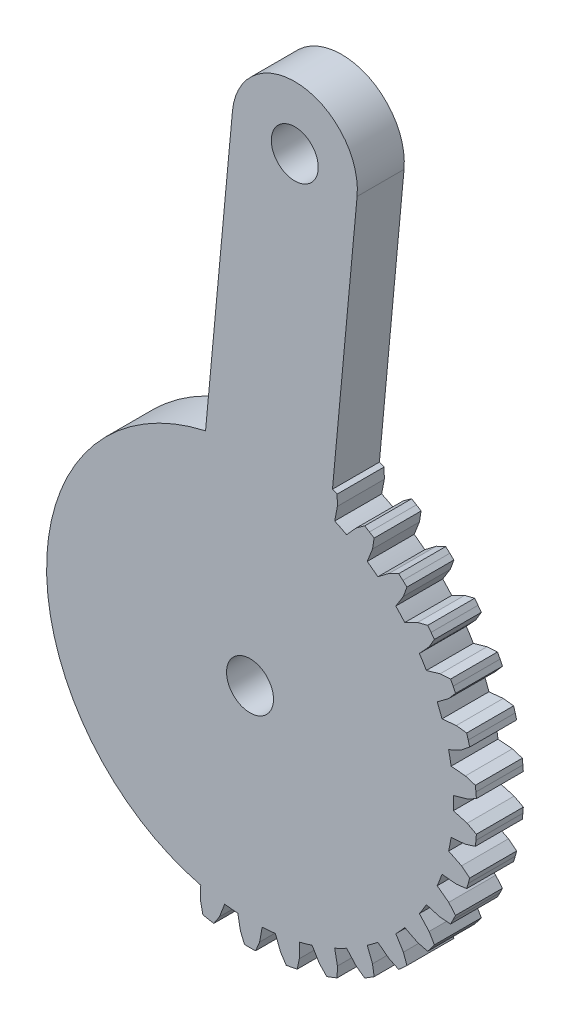
SolidWorks part; units mm, degrees
material "Chrome Stainless Steel"
ref_plane "Front Plane" through (0, 0, 0) normal (0, 0, 1) x (1, 0, 0)
ref_plane "Top Plane" through (0, 0, 0) normal (0, 1, 0) x (1, 0, 0)
ref_plane "Right Plane" through (0, 0, 0) normal (1, 0, 0) x (0, 0, -1)
sketch "Sketch1" plane through (0, 0, 0) normal (0, 0, 1) x (1, 0, 0)
  line L0 (0, 13) -> (0, 14.5) construction
  line L1 (-0.7768, 12.9768) -> (-0.6124, 13.879)
  line L2 (-0.6124, 13.879) -> (-0.3549, 14.4957)
  line L3 (-0.3549, 14.4957) -> (0, 14.5)
  line L4 (0.3549, 14.4957) -> (0, 14.5)
  line L5 (0.7768, 12.9768) -> (0.6124, 13.879)
  line L6 (0.6124, 13.879) -> (0.3549, 14.4957)
  line L7 (1.9483, 13.7552) -> (2.3147, 14.3141)
  line L8 (1.6209, 12.8986) -> (1.9483, 13.7552)
  line L9 (3.1522, 13.5302) -> (3.0124, 14.1836)
  line L10 (3.148, 12.6131) -> (3.1522, 13.5302)
  line L11 (3.0124, 14.1836) -> (2.6644, 14.2531)
  line L12 (2.3147, 14.3141) -> (2.6644, 14.2531)
  line L13 (4.4426, 13.163) -> (4.9055, 13.645)
  line L14 (3.9634, 12.3811) -> (4.4426, 13.163)
  line L15 (5.5847, 12.7206) -> (5.5674, 13.3886)
  line L16 (5.4121, 11.8199) -> (5.5847, 12.7206)
  line L17 (5.5674, 13.3886) -> (5.238, 13.5208)
  line L18 (4.9055, 13.645) -> (5.238, 13.5208)
  line L19 (6.7857, 12.1225) -> (7.3292, 12.5113)
  line L20 (6.1709, 11.442) -> (6.7857, 12.1225)
  line L21 (7.827, 11.4778) -> (7.9327, 12.1376)
  line L22 (7.4918, 10.6241) -> (7.827, 11.4778)
  line L23 (7.9327, 12.1376) -> (7.6333, 12.3281)
  line L24 (7.3292, 12.5113) -> (7.6333, 12.3281)
  line L25 (8.8977, 10.6693) -> (9.5034, 10.9515)
  line L26 (8.1683, 10.1133) -> (8.8977, 10.6693)
  line L27 (9.8028, 9.8441) -> (10.0279, 10.4733)
  line L28 (9.3165, 9.0666) -> (9.8028, 9.8441)
  line L29 (10.0279, 10.4733) -> (9.7686, 10.7156)
  line L30 (9.5034, 10.9515) -> (9.7686, 10.7156)
  line L31 (10.7066, 8.8526) -> (11.3539, 9.0188)
  line L32 (9.8876, 8.4402) -> (10.7066, 8.8526)
  line L33 (11.4447, 7.8753) -> (11.7817, 8.4524)
  line L34 (10.8238, 7.2004) -> (11.4447, 7.8753)
  line L35 (11.7817, 8.4524) -> (11.5712, 8.7382)
  line L36 (11.3539, 9.0188) -> (11.5712, 8.7382)
  line L37 (12.151, 6.7346) -> (12.8178, 6.779)
  line L38 (11.2701, 6.4796) -> (12.151, 6.7346)
  line L39 (12.6969, 5.6382) -> (13.1342, 6.1436)
  line L40 (11.9626, 5.0889) -> (12.6969, 5.6382)
  line L41 (13.1342, 6.1436) -> (12.9799, 6.4632)
  line L42 (12.8178, 6.779) -> (12.9799, 6.4632)
  line L43 (13.1816, 4.3872) -> (13.8452, 4.3083)
  line L44 (12.2688, 4.2984) -> (13.1816, 4.3872)
  line L45 (13.5168, 3.2092) -> (14.0394, 3.6256)
  line L46 (12.694, 2.8041) -> (13.5168, 3.2092)
  line L47 (14.0394, 3.6256) -> (13.9465, 3.9681)
  line L48 (13.8452, 4.3083) -> (13.9465, 3.9681)
  line L49 (13.7633, 1.8904) -> (14.4011, 1.6909)
  line L50 (12.8497, 1.9708) -> (13.7633, 1.8904)
  line L51 (13.8763, 0.6708) -> (14.4666, 0.9841)
  line L52 (12.9931, 0.4239) -> (13.8763, 0.6708)
  line L53 (14.4666, 0.9841) -> (14.4381, 1.3379)
  line L54 (14.4011, 1.6909) -> (14.4381, 1.3379)
  line L55 (13.8763, -0.6708) -> (14.4666, -0.9841)
  line L56 (12.9931, -0.4239) -> (13.8763, -0.6708)
  line L57 (13.7633, -1.8904) -> (14.4011, -1.6909)
  line L58 (12.8497, -1.9708) -> (13.7633, -1.8904)
  line L59 (14.4011, -1.6909) -> (14.4381, -1.3379)
  line L60 (14.4666, -0.9841) -> (14.4381, -1.3379)
  line L61 (13.5168, -3.2092) -> (14.0394, -3.6256)
  line L62 (12.694, -2.8041) -> (13.5168, -3.2092)
  line L63 (13.1816, -4.3872) -> (13.8452, -4.3083)
  line L64 (12.2688, -4.2984) -> (13.1816, -4.3872)
  line L65 (13.8452, -4.3083) -> (13.9465, -3.9681)
  line L66 (14.0394, -3.6256) -> (13.9465, -3.9681)
  line L67 (12.6969, -5.6382) -> (13.1342, -6.1436)
  line L68 (11.9626, -5.0889) -> (12.6969, -5.6382)
  line L69 (12.151, -6.7346) -> (12.8178, -6.779)
  line L70 (11.2701, -6.4796) -> (12.151, -6.7346)
  line L71 (12.8178, -6.779) -> (12.9799, -6.4632)
  line L72 (13.1342, -6.1436) -> (12.9799, -6.4632)
  line L73 (11.4447, -7.8753) -> (11.7817, -8.4524)
  line L74 (10.8238, -7.2004) -> (11.4447, -7.8753)
  line L75 (10.7066, -8.8526) -> (11.3539, -9.0188)
  line L76 (9.8876, -8.4402) -> (10.7066, -8.8526)
  line L77 (11.3539, -9.0188) -> (11.5712, -8.7382)
  line L78 (11.7817, -8.4524) -> (11.5712, -8.7382)
  line L79 (9.8028, -9.8441) -> (10.0279, -10.4733)
  line L80 (9.3165, -9.0666) -> (9.8028, -9.8441)
  line L81 (8.8977, -10.6693) -> (9.5034, -10.9515)
  line L82 (8.1683, -10.1133) -> (8.8977, -10.6693)
  line L83 (9.5034, -10.9515) -> (9.7686, -10.7156)
  line L84 (10.0279, -10.4733) -> (9.7686, -10.7156)
  line L85 (7.827, -11.4778) -> (7.9327, -12.1376)
  line L86 (7.4918, -10.6241) -> (7.827, -11.4778)
  line L87 (6.7857, -12.1225) -> (7.3292, -12.5113)
  line L88 (6.1709, -11.442) -> (6.7857, -12.1225)
  line L89 (7.3292, -12.5113) -> (7.6333, -12.3281)
  line L90 (7.9327, -12.1376) -> (7.6333, -12.3281)
  line L91 (5.5847, -12.7206) -> (5.5674, -13.3886)
  line L92 (5.4121, -11.8199) -> (5.5847, -12.7206)
  line L93 (4.4426, -13.163) -> (4.9055, -13.645)
  line L94 (3.9634, -12.3811) -> (4.4426, -13.163)
  line L95 (4.9055, -13.645) -> (5.238, -13.5208)
  line L96 (5.5674, -13.3886) -> (5.238, -13.5208)
  line L97 (3.1522, -13.5302) -> (3.0124, -14.1836)
  line L98 (3.148, -12.6131) -> (3.1522, -13.5302)
  line L99 (1.9483, -13.7552) -> (2.3147, -14.3141)
  line L100 (1.6209, -12.8986) -> (1.9483, -13.7552)
  line L101 (2.3147, -14.3141) -> (2.6644, -14.2531)
  line L102 (3.0124, -14.1836) -> (2.6644, -14.2531)
  line L103 (0.6124, -13.879) -> (0.3549, -14.4957)
  line L104 (0.7768, -12.9768) -> (0.6124, -13.879)
  line L105 (-0.6124, -13.879) -> (-0.3549, -14.4957)
  line L106 (-0.7768, -12.9768) -> (-0.6124, -13.879)
  line L107 (-0.3549, -14.4957) -> (0, -14.5)
  line L108 (0.3549, -14.4957) -> (0, -14.5)
  line L109 (-1.9483, -13.7552) -> (-2.3147, -14.3141)
  line L110 (-1.6209, -12.8986) -> (-1.9483, -13.7552)
  line L111 (-3.1522, -13.5302) -> (-3.0124, -14.1836)
  line L112 (-3.148, -12.6131) -> (-3.1522, -13.5302)
  line L113 (-3.0124, -14.1836) -> (-2.6644, -14.2531)
  line L114 (-2.3147, -14.3141) -> (-2.6644, -14.2531)
  line L115 (-4.4426, -13.163) -> (-4.9055, -13.645)
  line L116 (-3.9634, -12.3811) -> (-4.4426, -13.163)
  line L117 (-5.5847, -12.7206) -> (-5.5674, -13.3886)
  line L118 (-5.4121, -11.8199) -> (-5.5847, -12.7206)
  line L119 (-5.5674, -13.3886) -> (-5.238, -13.5208)
  line L120 (-4.9055, -13.645) -> (-5.238, -13.5208)
  line L121 (-6.7857, -12.1225) -> (-7.3292, -12.5113)
  line L122 (-6.1709, -11.442) -> (-6.7857, -12.1225)
  line L123 (-7.827, -11.4778) -> (-7.9327, -12.1376)
  line L124 (-7.4918, -10.6241) -> (-7.827, -11.4778)
  line L125 (-7.9327, -12.1376) -> (-7.6333, -12.3281)
  line L126 (-7.3292, -12.5113) -> (-7.6333, -12.3281)
  line L127 (-8.8977, -10.6693) -> (-9.5034, -10.9515)
  line L128 (-8.1683, -10.1133) -> (-8.8977, -10.6693)
  line L129 (-9.8028, -9.8441) -> (-10.0279, -10.4733)
  line L130 (-9.3165, -9.0666) -> (-9.8028, -9.8441)
  line L131 (-10.0279, -10.4733) -> (-9.7686, -10.7156)
  line L132 (-9.5034, -10.9515) -> (-9.7686, -10.7156)
  line L133 (-10.7066, -8.8526) -> (-11.3539, -9.0188)
  line L134 (-9.8876, -8.4402) -> (-10.7066, -8.8526)
  line L135 (-11.4447, -7.8753) -> (-11.7817, -8.4524)
  line L136 (-10.8238, -7.2004) -> (-11.4447, -7.8753)
  line L137 (-11.7817, -8.4524) -> (-11.5712, -8.7382)
  line L138 (-11.3539, -9.0188) -> (-11.5712, -8.7382)
  line L139 (-12.151, -6.7346) -> (-12.8178, -6.779)
  line L140 (-11.2701, -6.4796) -> (-12.151, -6.7346)
  line L141 (-12.6969, -5.6382) -> (-13.1342, -6.1436)
  line L142 (-11.9626, -5.0889) -> (-12.6969, -5.6382)
  line L143 (-13.1342, -6.1436) -> (-12.9799, -6.4632)
  line L144 (-12.8178, -6.779) -> (-12.9799, -6.4632)
  line L145 (-13.1816, -4.3872) -> (-13.8452, -4.3083)
  line L146 (-12.2688, -4.2984) -> (-13.1816, -4.3872)
  line L147 (-13.5168, -3.2092) -> (-14.0394, -3.6256)
  line L148 (-12.694, -2.8041) -> (-13.5168, -3.2092)
  line L149 (-14.0394, -3.6256) -> (-13.9465, -3.9681)
  line L150 (-13.8452, -4.3083) -> (-13.9465, -3.9681)
  line L151 (-13.7633, -1.8904) -> (-14.4011, -1.6909)
  line L152 (-12.8497, -1.9708) -> (-13.7633, -1.8904)
  line L153 (-13.8763, -0.6708) -> (-14.4666, -0.9841)
  line L154 (-12.9931, -0.4239) -> (-13.8763, -0.6708)
  line L155 (-14.4666, -0.9841) -> (-14.4381, -1.3379)
  line L156 (-14.4011, -1.6909) -> (-14.4381, -1.3379)
  line L157 (-13.8763, 0.6708) -> (-14.4666, 0.9841)
  line L158 (-12.9931, 0.4239) -> (-13.8763, 0.6708)
  line L159 (-13.7633, 1.8904) -> (-14.4011, 1.6909)
  line L160 (-12.8497, 1.9708) -> (-13.7633, 1.8904)
  line L161 (-14.4011, 1.6909) -> (-14.4381, 1.3379)
  line L162 (-14.4666, 0.9841) -> (-14.4381, 1.3379)
  line L163 (-13.5168, 3.2092) -> (-14.0394, 3.6256)
  line L164 (-12.694, 2.8041) -> (-13.5168, 3.2092)
  line L165 (-13.1816, 4.3872) -> (-13.8452, 4.3083)
  line L166 (-12.2688, 4.2984) -> (-13.1816, 4.3872)
  line L167 (-13.8452, 4.3083) -> (-13.9465, 3.9681)
  line L168 (-14.0394, 3.6256) -> (-13.9465, 3.9681)
  line L169 (-12.6969, 5.6382) -> (-13.1342, 6.1436)
  line L170 (-11.9626, 5.0889) -> (-12.6969, 5.6382)
  line L171 (-12.151, 6.7346) -> (-12.8178, 6.779)
  line L172 (-11.2701, 6.4796) -> (-12.151, 6.7346)
  line L173 (-12.8178, 6.779) -> (-12.9799, 6.4632)
  line L174 (-13.1342, 6.1436) -> (-12.9799, 6.4632)
  line L175 (-11.4447, 7.8753) -> (-11.7817, 8.4524)
  line L176 (-10.8238, 7.2004) -> (-11.4447, 7.8753)
  line L177 (-10.7066, 8.8526) -> (-11.3539, 9.0188)
  line L178 (-9.8876, 8.4402) -> (-10.7066, 8.8526)
  line L179 (-11.3539, 9.0188) -> (-11.5712, 8.7382)
  line L180 (-11.7817, 8.4524) -> (-11.5712, 8.7382)
  line L181 (-9.8028, 9.8441) -> (-10.0279, 10.4733)
  line L182 (-9.3165, 9.0666) -> (-9.8028, 9.8441)
  line L183 (-8.8977, 10.6693) -> (-9.5034, 10.9515)
  line L184 (-8.1683, 10.1133) -> (-8.8977, 10.6693)
  line L185 (-9.5034, 10.9515) -> (-9.7686, 10.7156)
  line L186 (-10.0279, 10.4733) -> (-9.7686, 10.7156)
  line L187 (-7.827, 11.4778) -> (-7.9327, 12.1376)
  line L188 (-7.4918, 10.6241) -> (-7.827, 11.4778)
  line L189 (-6.7857, 12.1225) -> (-7.3292, 12.5113)
  line L190 (-6.1709, 11.442) -> (-6.7857, 12.1225)
  line L191 (-7.3292, 12.5113) -> (-7.6333, 12.3281)
  line L192 (-7.9327, 12.1376) -> (-7.6333, 12.3281)
  line L193 (-5.5847, 12.7206) -> (-5.5674, 13.3886)
  line L194 (-5.4121, 11.8199) -> (-5.5847, 12.7206)
  line L195 (-4.4426, 13.163) -> (-4.9055, 13.645)
  line L196 (-3.9634, 12.3811) -> (-4.4426, 13.163)
  line L197 (-4.9055, 13.645) -> (-5.238, 13.5208)
  line L198 (-5.5674, 13.3886) -> (-5.238, 13.5208)
  line L199 (-3.1522, 13.5302) -> (-3.0124, 14.1836)
  line L200 (-3.148, 12.6131) -> (-3.1522, 13.5302)
  line L201 (-1.9483, 13.7552) -> (-2.3147, 14.3141)
  line L202 (-1.6209, 12.8986) -> (-1.9483, 13.7552)
  line L203 (-2.3147, 14.3141) -> (-2.6644, 14.2531)
  line L204 (-3.0124, 14.1836) -> (-2.6644, 14.2531)
  circle A0 centre (0, 0) radius 13
  circle A1 centre (0, 0) radius 14.5
  point P12 (0, 0)
  point P13 (0, 0)
  point P246 (0, 0)
  dimension "D1" = 29
  dimension "D2" = 26
  dimension "D3" = 0.3549
  dimension "D4" = 0.6682
  dimension "D5" = 0.9171
  dimension "D7" = 1.3359
  dimension "D8" = 0.8441
  dimension "D9" = 2.6758
  dimension "D6" = 34
extrude "Boss-Extrude1" add sketch "Sketch1" along normal blind 3
sketch "Sketch2" plane through (0, 0, 3) normal (0, 0, 1) x (1, 0, 0)
  circle A0 centre (0, 0) radius 1.5
  dimension "D1" = 3
extrude "Cut-Extrude1" cut sketch "Sketch2" against normal blind 7
sketch "Sketch4" plane through (0, 0, 3) normal (0, 0, 1) x (1, 0, 0)
  line L0 (0, 0) -> (2.8603, 30.8678) construction
  line L1 (-3.9829, 0.3691) -> (-1.1226, 31.2368)
  line L2 (3.9829, -0.3691) -> (6.8433, 30.4987)
  line L3 (0, 0) -> (14.4381, -1.3379) construction
  line L117 (0.3549, 14.4957) -> (0, 14.5)
  line L118 (0, 14.5) -> (-0.3549, 14.4957)
  line L119 (-0.3549, 14.4957) -> (-0.6124, 13.879)
  line L120 (-0.6124, 13.879) -> (-0.7768, 12.9768)
  line L121 (-3.148, -12.6131) -> (-3.1522, -13.5302)
  line L122 (-3.1522, -13.5302) -> (-3.0124, -14.1836)
  line L123 (-3.0124, -14.1836) -> (-2.6644, -14.2531)
  line L124 (-2.6644, -14.2531) -> (-2.3147, -14.3141)
  line L125 (-2.3147, -14.3141) -> (-1.9483, -13.7552)
  line L126 (-1.9483, -13.7552) -> (-1.6209, -12.8986)
  line L127 (-0.7768, -12.9768) -> (-0.6124, -13.879)
  line L128 (-0.6124, -13.879) -> (-0.3549, -14.4957)
  line L129 (-0.3549, -14.4957) -> (0, -14.5)
  line L130 (0, -14.5) -> (0.3549, -14.4957)
  line L131 (0.3549, -14.4957) -> (0.6124, -13.879)
  line L132 (0.6124, -13.879) -> (0.7768, -12.9768)
  line L133 (1.6209, -12.8986) -> (1.9483, -13.7552)
  line L134 (1.9483, -13.7552) -> (2.3147, -14.3141)
  line L135 (2.3147, -14.3141) -> (2.6644, -14.2531)
  line L136 (2.6644, -14.2531) -> (3.0124, -14.1836)
  line L137 (3.0124, -14.1836) -> (3.1522, -13.5302)
  line L138 (3.1522, -13.5302) -> (3.148, -12.6131)
  line L139 (3.9634, -12.3811) -> (4.4426, -13.163)
  line L140 (4.4426, -13.163) -> (4.9055, -13.645)
  line L141 (4.9055, -13.645) -> (5.238, -13.5208)
  line L142 (5.238, -13.5208) -> (5.5674, -13.3886)
  line L143 (5.5674, -13.3886) -> (5.5847, -12.7206)
  line L144 (5.5847, -12.7206) -> (5.4121, -11.8199)
  line L145 (6.1709, -11.442) -> (6.7857, -12.1225)
  line L146 (6.7857, -12.1225) -> (7.3292, -12.5113)
  line L147 (7.3292, -12.5113) -> (7.6333, -12.3281)
  line L148 (7.6333, -12.3281) -> (7.9327, -12.1376)
  line L149 (7.9327, -12.1376) -> (7.827, -11.4778)
  line L150 (7.827, -11.4778) -> (7.4918, -10.6241)
  line L151 (8.1683, -10.1133) -> (8.8977, -10.6693)
  line L152 (8.8977, -10.6693) -> (9.5034, -10.9515)
  line L153 (9.5034, -10.9515) -> (9.7686, -10.7156)
  line L154 (9.7686, -10.7156) -> (10.0279, -10.4733)
  line L155 (10.0279, -10.4733) -> (9.8028, -9.8441)
  line L156 (9.8028, -9.8441) -> (9.3165, -9.0666)
  line L157 (9.8876, -8.4402) -> (10.7066, -8.8526)
  line L158 (10.7066, -8.8526) -> (11.3539, -9.0188)
  line L159 (11.3539, -9.0188) -> (11.5712, -8.7382)
  line L160 (11.5712, -8.7382) -> (11.7817, -8.4524)
  line L161 (11.7817, -8.4524) -> (11.4447, -7.8753)
  line L162 (11.4447, -7.8753) -> (10.8238, -7.2004)
  line L163 (11.2701, -6.4796) -> (12.151, -6.7346)
  line L164 (12.151, -6.7346) -> (12.8178, -6.779)
  line L165 (12.8178, -6.779) -> (12.9799, -6.4632)
  line L166 (12.9799, -6.4632) -> (13.1342, -6.1436)
  line L167 (13.1342, -6.1436) -> (12.6969, -5.6382)
  line L168 (12.6969, -5.6382) -> (11.9626, -5.0889)
  line L169 (12.2688, -4.2984) -> (13.1816, -4.3872)
  line L170 (13.1816, -4.3872) -> (13.8452, -4.3083)
  line L171 (13.8452, -4.3083) -> (13.9465, -3.9681)
  line L172 (13.9465, -3.9681) -> (14.0394, -3.6256)
  line L173 (14.0394, -3.6256) -> (13.5168, -3.2092)
  line L174 (13.5168, -3.2092) -> (12.694, -2.8041)
  line L175 (12.8497, -1.9708) -> (13.7633, -1.8904)
  line L176 (13.7633, -1.8904) -> (14.4011, -1.6909)
  line L177 (14.4011, -1.6909) -> (14.4381, -1.3379)
  line L178 (14.4381, -1.3379) -> (14.4666, -0.9841)
  line L179 (14.4666, -0.9841) -> (13.8763, -0.6708)
  line L180 (13.8763, -0.6708) -> (12.9931, -0.4239)
  line L181 (12.9931, 0.4239) -> (13.8763, 0.6708)
  line L182 (13.8763, 0.6708) -> (14.4666, 0.9841)
  line L183 (14.4666, 0.9841) -> (14.4381, 1.3379)
  line L184 (14.4381, 1.3379) -> (14.4011, 1.6909)
  line L185 (14.4011, 1.6909) -> (13.7633, 1.8904)
  line L186 (13.7633, 1.8904) -> (12.8497, 1.9708)
  line L187 (12.694, 2.8041) -> (13.5168, 3.2092)
  line L188 (13.5168, 3.2092) -> (14.0394, 3.6256)
  line L189 (14.0394, 3.6256) -> (13.9465, 3.9681)
  line L190 (13.9465, 3.9681) -> (13.8452, 4.3083)
  line L191 (13.8452, 4.3083) -> (13.1816, 4.3872)
  line L192 (13.1816, 4.3872) -> (12.2688, 4.2984)
  line L193 (11.9626, 5.0889) -> (12.6969, 5.6382)
  line L194 (12.6969, 5.6382) -> (13.1342, 6.1436)
  line L195 (13.1342, 6.1436) -> (12.9799, 6.4632)
  line L196 (12.9799, 6.4632) -> (12.8178, 6.779)
  line L197 (12.8178, 6.779) -> (12.151, 6.7346)
  line L198 (12.151, 6.7346) -> (11.2701, 6.4796)
  line L199 (10.8238, 7.2004) -> (11.4447, 7.8753)
  line L200 (11.4447, 7.8753) -> (11.7817, 8.4524)
  line L201 (11.7817, 8.4524) -> (11.5712, 8.7382)
  line L202 (11.5712, 8.7382) -> (11.3539, 9.0188)
  line L203 (11.3539, 9.0188) -> (10.7066, 8.8526)
  line L204 (10.7066, 8.8526) -> (9.8876, 8.4402)
  line L205 (9.3165, 9.0666) -> (9.8028, 9.8441)
  line L206 (9.8028, 9.8441) -> (10.0279, 10.4733)
  line L207 (10.0279, 10.4733) -> (9.7686, 10.7156)
  line L208 (9.7686, 10.7156) -> (9.5034, 10.9515)
  line L209 (9.5034, 10.9515) -> (8.8977, 10.6693)
  line L210 (8.8977, 10.6693) -> (8.1683, 10.1133)
  line L211 (7.4918, 10.6241) -> (7.827, 11.4778)
  line L212 (7.827, 11.4778) -> (7.9327, 12.1376)
  line L213 (7.9327, 12.1376) -> (7.6333, 12.3281)
  line L214 (7.6333, 12.3281) -> (7.3292, 12.5113)
  line L215 (7.3292, 12.5113) -> (6.7857, 12.1225)
  line L216 (6.7857, 12.1225) -> (6.1709, 11.442)
  line L217 (5.4121, 11.8199) -> (5.5847, 12.7206)
  line L218 (5.5847, 12.7206) -> (5.5674, 13.3886)
  line L219 (5.5674, 13.3886) -> (5.238, 13.5208)
  line L220 (5.238, 13.5208) -> (4.9055, 13.645)
  line L221 (4.9055, 13.645) -> (4.4426, 13.163)
  line L222 (4.4426, 13.163) -> (3.9634, 12.3811)
  line L223 (3.148, 12.6131) -> (3.1522, 13.5302)
  line L224 (3.1522, 13.5302) -> (3.0124, 14.1836)
  line L225 (3.0124, 14.1836) -> (2.6644, 14.2531)
  line L226 (2.6644, 14.2531) -> (2.3147, 14.3141)
  line L227 (2.3147, 14.3141) -> (1.9483, 13.7552)
  line L228 (1.9483, 13.7552) -> (1.6209, 12.8986)
  line L229 (0.7768, 12.9768) -> (0.6124, 13.879)
  line L230 (0.6124, 13.879) -> (0.3549, 14.4957)
  line L231 (0.3549, 14.4957) -> (0, 14.5)
  line L232 (0, 14.5) -> (-0.3549, 14.4957)
  line L233 (-0.3549, 14.4957) -> (-0.6124, 13.879)
  line L234 (-0.6124, 13.879) -> (-0.7768, 12.9768)
  line L235 (-3.148, -12.6131) -> (-3.1522, -13.5302)
  line L236 (-3.1522, -13.5302) -> (-3.0124, -14.1836)
  line L237 (-3.0124, -14.1836) -> (-2.6644, -14.2531)
  line L238 (-2.6644, -14.2531) -> (-2.3147, -14.3141)
  line L239 (-2.3147, -14.3141) -> (-1.9483, -13.7552)
  line L240 (-1.9483, -13.7552) -> (-1.6209, -12.8986)
  line L241 (-0.7768, -12.9768) -> (-0.6124, -13.879)
  line L242 (-0.6124, -13.879) -> (-0.3549, -14.4957)
  line L243 (-0.3549, -14.4957) -> (0, -14.5)
  line L244 (0, -14.5) -> (0.3549, -14.4957)
  line L245 (0.3549, -14.4957) -> (0.6124, -13.879)
  line L246 (0.6124, -13.879) -> (0.7768, -12.9768)
  line L247 (1.6209, -12.8986) -> (1.9483, -13.7552)
  line L248 (1.9483, -13.7552) -> (2.3147, -14.3141)
  line L249 (2.3147, -14.3141) -> (2.6644, -14.2531)
  line L250 (2.6644, -14.2531) -> (3.0124, -14.1836)
  line L251 (3.0124, -14.1836) -> (3.1522, -13.5302)
  line L252 (3.1522, -13.5302) -> (3.148, -12.6131)
  line L253 (3.9634, -12.3811) -> (4.4426, -13.163)
  line L254 (4.4426, -13.163) -> (4.9055, -13.645)
  line L255 (4.9055, -13.645) -> (5.238, -13.5208)
  line L256 (5.238, -13.5208) -> (5.5674, -13.3886)
  line L257 (5.5674, -13.3886) -> (5.5847, -12.7206)
  line L258 (5.5847, -12.7206) -> (5.4121, -11.8199)
  line L259 (6.1709, -11.442) -> (6.7857, -12.1225)
  line L260 (6.7857, -12.1225) -> (7.3292, -12.5113)
  line L261 (7.3292, -12.5113) -> (7.6333, -12.3281)
  line L262 (7.6333, -12.3281) -> (7.9327, -12.1376)
  line L263 (7.9327, -12.1376) -> (7.827, -11.4778)
  line L264 (7.827, -11.4778) -> (7.4918, -10.6241)
  line L265 (8.1683, -10.1133) -> (8.8977, -10.6693)
  line L266 (8.8977, -10.6693) -> (9.5034, -10.9515)
  line L267 (9.5034, -10.9515) -> (9.7686, -10.7156)
  line L268 (9.7686, -10.7156) -> (10.0279, -10.4733)
  line L269 (10.0279, -10.4733) -> (9.8028, -9.8441)
  line L270 (9.8028, -9.8441) -> (9.3165, -9.0666)
  line L271 (9.8876, -8.4402) -> (10.7066, -8.8526)
  line L272 (10.7066, -8.8526) -> (11.3539, -9.0188)
  line L273 (11.3539, -9.0188) -> (11.5712, -8.7382)
  line L274 (11.5712, -8.7382) -> (11.7817, -8.4524)
  line L275 (11.7817, -8.4524) -> (11.4447, -7.8753)
  line L276 (11.4447, -7.8753) -> (10.8238, -7.2004)
  line L277 (11.2701, -6.4796) -> (12.151, -6.7346)
  line L278 (12.151, -6.7346) -> (12.8178, -6.779)
  line L279 (12.8178, -6.779) -> (12.9799, -6.4632)
  line L280 (12.9799, -6.4632) -> (13.1342, -6.1436)
  line L281 (13.1342, -6.1436) -> (12.6969, -5.6382)
  line L282 (12.6969, -5.6382) -> (11.9626, -5.0889)
  line L283 (12.2688, -4.2984) -> (13.1816, -4.3872)
  line L284 (13.1816, -4.3872) -> (13.8452, -4.3083)
  line L285 (13.8452, -4.3083) -> (13.9465, -3.9681)
  line L286 (13.9465, -3.9681) -> (14.0394, -3.6256)
  line L287 (14.0394, -3.6256) -> (13.5168, -3.2092)
  line L288 (13.5168, -3.2092) -> (12.694, -2.8041)
  line L289 (12.8497, -1.9708) -> (13.7633, -1.8904)
  line L290 (13.7633, -1.8904) -> (14.4011, -1.6909)
  line L291 (14.4011, -1.6909) -> (14.4381, -1.3379)
  line L292 (14.4381, -1.3379) -> (14.4666, -0.9841)
  line L293 (14.4666, -0.9841) -> (13.8763, -0.6708)
  line L294 (13.8763, -0.6708) -> (12.9931, -0.4239)
  line L295 (12.9931, 0.4239) -> (13.8763, 0.6708)
  line L296 (13.8763, 0.6708) -> (14.4666, 0.9841)
  line L297 (14.4666, 0.9841) -> (14.4381, 1.3379)
  line L298 (14.4381, 1.3379) -> (14.4011, 1.6909)
  line L299 (14.4011, 1.6909) -> (13.7633, 1.8904)
  line L300 (13.7633, 1.8904) -> (12.8497, 1.9708)
  line L301 (12.694, 2.8041) -> (13.5168, 3.2092)
  line L302 (13.5168, 3.2092) -> (14.0394, 3.6256)
  line L303 (14.0394, 3.6256) -> (13.9465, 3.9681)
  line L304 (13.9465, 3.9681) -> (13.8452, 4.3083)
  line L305 (13.8452, 4.3083) -> (13.1816, 4.3872)
  line L306 (13.1816, 4.3872) -> (12.2688, 4.2984)
  line L307 (11.9626, 5.0889) -> (12.6969, 5.6382)
  line L308 (12.6969, 5.6382) -> (13.1342, 6.1436)
  line L309 (13.1342, 6.1436) -> (12.9799, 6.4632)
  line L310 (12.9799, 6.4632) -> (12.8178, 6.779)
  line L311 (12.8178, 6.779) -> (12.151, 6.7346)
  line L312 (12.151, 6.7346) -> (11.2701, 6.4796)
  line L313 (10.8238, 7.2004) -> (11.4447, 7.8753)
  line L314 (11.4447, 7.8753) -> (11.7817, 8.4524)
  line L315 (11.7817, 8.4524) -> (11.5712, 8.7382)
  line L316 (11.5712, 8.7382) -> (11.3539, 9.0188)
  line L317 (11.3539, 9.0188) -> (10.7066, 8.8526)
  line L318 (10.7066, 8.8526) -> (9.8876, 8.4402)
  line L319 (9.3165, 9.0666) -> (9.8028, 9.8441)
  line L320 (9.8028, 9.8441) -> (10.0279, 10.4733)
  line L321 (10.0279, 10.4733) -> (9.7686, 10.7156)
  line L322 (9.7686, 10.7156) -> (9.5034, 10.9515)
  line L323 (9.5034, 10.9515) -> (8.8977, 10.6693)
  line L324 (8.8977, 10.6693) -> (8.1683, 10.1133)
  line L325 (7.4918, 10.6241) -> (7.827, 11.4778)
  line L326 (7.827, 11.4778) -> (7.9327, 12.1376)
  line L327 (7.9327, 12.1376) -> (7.6333, 12.3281)
  line L328 (7.6333, 12.3281) -> (7.3292, 12.5113)
  line L329 (7.3292, 12.5113) -> (6.7857, 12.1225)
  line L330 (6.7857, 12.1225) -> (6.1709, 11.442)
  line L331 (5.4121, 11.8199) -> (5.5847, 12.7206)
  line L332 (5.5847, 12.7206) -> (5.5674, 13.3886)
  line L333 (5.5674, 13.3886) -> (5.238, 13.5208)
  line L334 (5.238, 13.5208) -> (4.9055, 13.645)
  line L335 (4.9055, 13.645) -> (4.4426, 13.163)
  line L336 (4.4426, 13.163) -> (3.9634, 12.3811)
  line L337 (3.148, 12.6131) -> (3.1522, 13.5302)
  line L338 (3.1522, 13.5302) -> (3.0124, 14.1836)
  line L339 (3.0124, 14.1836) -> (2.6644, 14.2531)
  line L340 (2.6644, 14.2531) -> (2.3147, 14.3141)
  line L341 (2.3147, 14.3141) -> (1.9483, 13.7552)
  line L342 (1.9483, 13.7552) -> (1.6209, 12.8986)
  line L343 (0.7768, 12.9768) -> (0.6124, 13.879)
  line L344 (0.6124, 13.879) -> (0.3549, 14.4957)
  arc A0 (-3.9829, 0.3691) -> (3.9829, -0.3691) centre (0, 0) ccw
  arc A1 (6.8433, 30.4987) -> (-1.1226, 31.2368) centre (2.8603, 30.8678) ccw
  circle A2 centre (2.8603, 30.8678) radius 1.5
  circle A3 centre (0, 0) radius 1.5
  arc A22 (-0.7768, 12.9768) -> (-3.148, -12.6131) centre (0, 0) ccw
  arc A23 (-1.6209, -12.8986) -> (-0.7768, -12.9768) centre (0, 0) ccw
  arc A24 (0.7768, -12.9768) -> (1.6209, -12.8986) centre (0, 0) ccw
  arc A25 (3.148, -12.6131) -> (3.9634, -12.3811) centre (0, 0) ccw
  arc A26 (5.4121, -11.8199) -> (6.1709, -11.442) centre (0, 0) ccw
  arc A27 (7.4918, -10.6241) -> (8.1683, -10.1133) centre (0, 0) ccw
  arc A28 (9.3165, -9.0666) -> (9.8876, -8.4402) centre (0, 0) ccw
  arc A29 (10.8238, -7.2004) -> (11.2701, -6.4796) centre (0, 0) ccw
  arc A30 (11.9626, -5.0889) -> (12.2688, -4.2984) centre (0, 0) ccw
  arc A31 (12.694, -2.8041) -> (12.8497, -1.9708) centre (0, 0) ccw
  arc A32 (12.9931, -0.4239) -> (12.9931, 0.4239) centre (0, 0) ccw
  arc A33 (12.8497, 1.9708) -> (12.694, 2.8041) centre (0, 0) ccw
  arc A34 (12.2688, 4.2984) -> (11.9626, 5.0889) centre (0, 0) ccw
  arc A35 (11.2701, 6.4796) -> (10.8238, 7.2004) centre (0, 0) ccw
  arc A36 (9.8876, 8.4402) -> (9.3165, 9.0666) centre (0, 0) ccw
  arc A37 (8.1683, 10.1133) -> (7.4918, 10.6241) centre (0, 0) ccw
  arc A38 (6.1709, 11.442) -> (5.4121, 11.8199) centre (0, 0) ccw
  arc A39 (3.9634, 12.3811) -> (3.148, 12.6131) centre (0, 0) ccw
  arc A40 (1.6209, 12.8986) -> (0.7768, 12.9768) centre (0, 0) ccw
  arc A41 (-0.7768, 12.9768) -> (-3.148, -12.6131) centre (0, 0) ccw
  arc A42 (-1.6209, -12.8986) -> (-0.7768, -12.9768) centre (0, 0) ccw
  arc A43 (0.7768, -12.9768) -> (1.6209, -12.8986) centre (0, 0) ccw
  arc A44 (3.148, -12.6131) -> (3.9634, -12.3811) centre (0, 0) ccw
  arc A45 (5.4121, -11.8199) -> (6.1709, -11.442) centre (0, 0) ccw
  arc A46 (7.4918, -10.6241) -> (8.1683, -10.1133) centre (0, 0) ccw
  arc A47 (9.3165, -9.0666) -> (9.8876, -8.4402) centre (0, 0) ccw
  arc A48 (10.8238, -7.2004) -> (11.2701, -6.4796) centre (0, 0) ccw
  arc A49 (11.9626, -5.0889) -> (12.2688, -4.2984) centre (0, 0) ccw
  arc A50 (12.694, -2.8041) -> (12.8497, -1.9708) centre (0, 0) ccw
  arc A51 (12.9931, -0.4239) -> (12.9931, 0.4239) centre (0, 0) ccw
  arc A52 (12.8497, 1.9708) -> (12.694, 2.8041) centre (0, 0) ccw
  arc A53 (12.2688, 4.2984) -> (11.9626, 5.0889) centre (0, 0) ccw
  arc A54 (11.2701, 6.4796) -> (10.8238, 7.2004) centre (0, 0) ccw
  arc A55 (9.8876, 8.4402) -> (9.3165, 9.0666) centre (0, 0) ccw
  arc A56 (8.1683, 10.1133) -> (7.4918, 10.6241) centre (0, 0) ccw
  arc A57 (6.1709, 11.442) -> (5.4121, 11.8199) centre (0, 0) ccw
  arc A58 (3.9634, 12.3811) -> (3.148, 12.6131) centre (0, 0) ccw
  arc A59 (1.6209, 12.8986) -> (0.7768, 12.9768) centre (0, 0) ccw
  point P3 (1.4302, 15.4339)
  dimension "D3" = 3
  dimension "D5" = 3
  dimension "D1" = 8
  dimension "D2" = 31
  dimension "D4" = 0
extrude "Boss-Extrude4" add sketch "Sketch4" against normal blind 3
